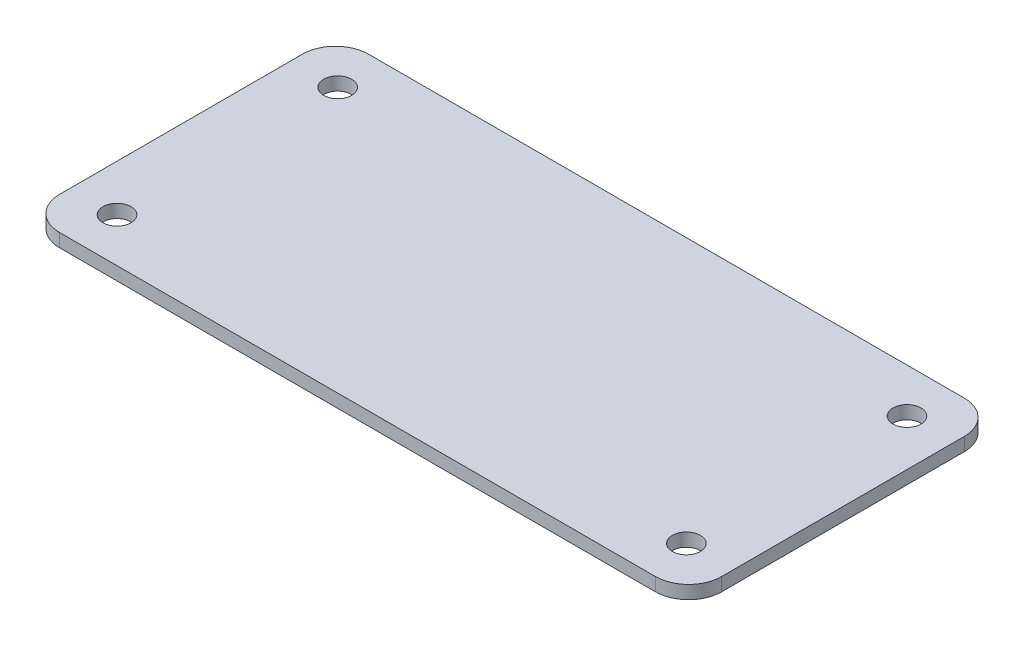
SolidWorks part; units mm, degrees
ref_plane "Front" through (0, 0, 0) normal (0, 0, 1) x (1, 0, 0)
ref_plane "Top" through (0, 0, 0) normal (0, 1, 0) x (1, 0, 0)
ref_plane "Right" through (0, 0, 0) normal (1, 0, 0) x (0, 0, -1)
sketch "Esboço2" plane through (0, 0, 0) normal (0, 1, 0) x (1, 0, 0)
  line L1 (0, 0) -> (150, 0)
  line L2 (0, 0) -> (0, 70)
  line L3 (0, 70) -> (150, 70)
  line L4 (150, 0) -> (150, 70)
extrude "Ressalto-extrusão1" add sketch "Esboço2" along normal blind 3
sketch "Esboço4" plane through (0, 3, 0) normal (0, 1, 0) x (1, 0, 0)
  line L0 (0, 70) -> (10.5, 70)
  line L1 (150, 70) -> (0, 70) construction
  line L2 (10.5, 70) -> (10.5, 60)
  line L3 (150, 70) -> (139.5, 70)
  line L4 (139.5, 70) -> (139.5, 60)
  line L5 (10.5, 0) -> (10.5, 10)
  line L6 (0, 0) -> (150, 0) construction
  line L7 (139.5, 0) -> (139.5, 10)
  circle A0 centre (10.5, 60) radius 3.175
  circle A1 centre (139.5, 60) radius 3.175
  circle A2 centre (139.5, 10) radius 3.175
  circle A3 centre (10.5, 10) radius 3.175
  dimension "D1" = 2
  dimension "D3" = 50
  dimension "D4" = 129
  dimension "D2" = 2
extrude "Corte-extrusão1" cut sketch "Esboço4" against normal blind 3
fillet "Filete1" radius 7.5 4 edges at (0, 1.5, 0) (150, 1.5, 0) (150, 1.5, -70) (0, 1.5, -70)
